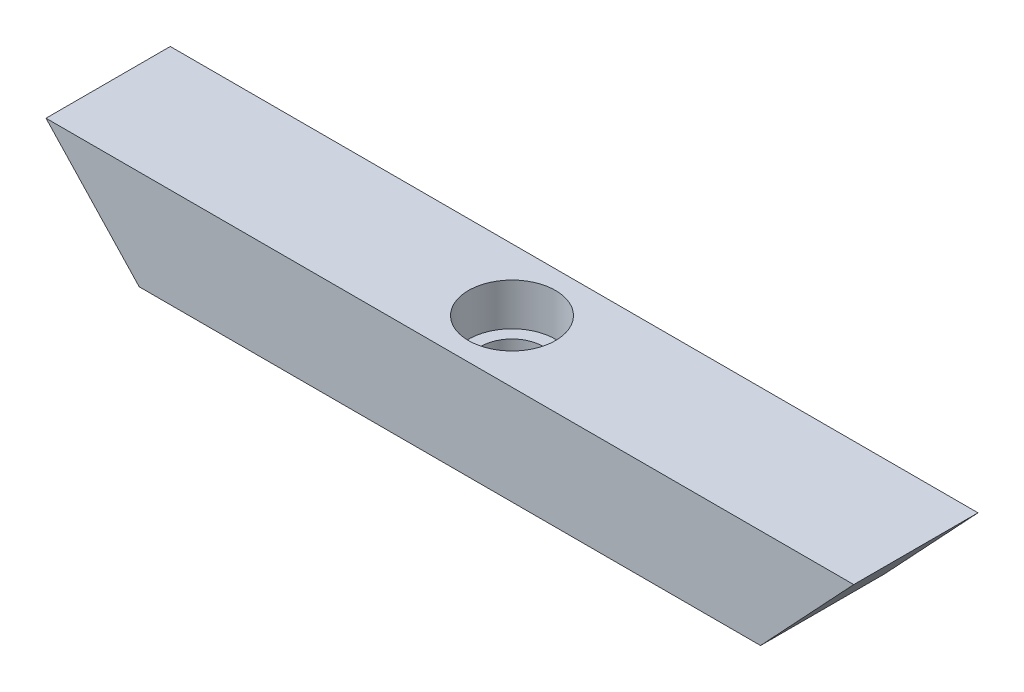
SolidWorks part; units mm, degrees
ref_plane "Front Plane" through (0, 0, 0) normal (0, 0, 1) x (1, 0, 0)
ref_plane "Top Plane" through (0, 0, 0) normal (0, 1, 0) x (1, 0, 0)
ref_plane "Right Plane" through (0, 0, 0) normal (1, 0, 0) x (0, 0, -1)
sketch "Sketch1" plane through (0, 0, 0) normal (0, 0, 1) x (1, 0, 0)
  line L0 (-162.5, 0) -> (162.5, 0)
  line L1 (162.5, 0) -> (125, -40)
  line L2 (125, -40) -> (-125, -40)
  line L3 (0, -22) -> (0, 22) construction
  line L4 (-162.5, 0) -> (-125, -40)
  point P8 (0, -40)
  point P9 (0, 0)
  dimension "D1" = 250
  dimension "D2" = 325
  dimension "D3" = 40
extrude "Boss-Extrude1" add sketch "Sketch1" along normal blind 50
sketch "Sketch2" plane through (0, 0, 0) normal (0, 1, 0) x (1, 0, 0)
  line L1 (162.5, -50) -> (-162.5, -50) construction
  circle A0 centre (0, -25) radius 17.5
  dimension "D1" = 35
  dimension "D2" = 25
extrude "Cut-Extrude1" cut sketch "Sketch2" against normal up to next
ref_plane "Plane1" through (0, -20, 0) normal (0, 1, 0) x (1, 0, 0)
sketch "Sketch3" plane through (0, -20, 0) normal (0, 1, 0) x (1, 0, 0)
  circle A0 centre (0, -25) radius 17.5 construction
  circle A1 centre (0, -25) radius 17.5
  circle A2 centre (0, -25) radius 12.5
  dimension "D1" = 5
extrude "Boss-Extrude2" add sketch "Sketch3" along normal blind 3 and the other way blind 3
